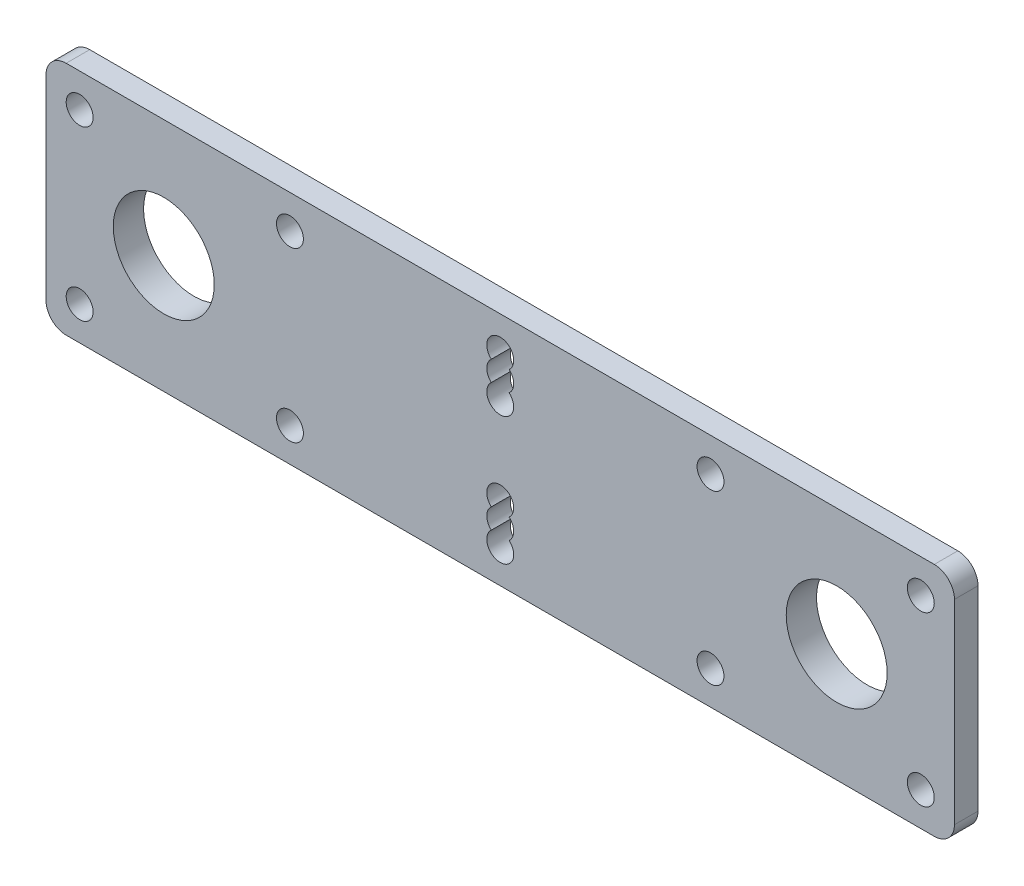
SolidWorks part; units mm, degrees
ref_plane "Ön Düzlem" through (0, 0, 0) normal (0, 0, 1) x (1, 0, 0)
ref_plane "Üst Düzlem" through (0, 0, 0) normal (0, 1, 0) x (1, 0, 0)
ref_plane "Sağ Düzlem" through (0, 0, 0) normal (1, 0, 0) x (0, 0, -1)
sketch "Sketch1" plane through (0, 0, 0) normal (0, 0, 1) x (1, 0, 0)
  line L1 (-135, 35) -> (135, 35)
  line L2 (-135, 35) -> (-135, -35)
  line L3 (-135, -35) -> (135, -35)
  line L4 (135, 35) -> (135, -35)
  line L5 (-135, 35) -> (135, -35) construction
  line L6 (-135, -35) -> (135, 35) construction
  point P0 (0, 0)
  dimension "D1" = 70
  dimension "D2" = 270
extrude "Boss-Extrude1" add sketch "Sketch1" along normal blind 7
fillet "Fillet1" radius 6 4 edges at (135, -35, 3.5) (135, 35, 3.5) (-135, -35, 3.5) (-135, 35, 3.5)
sketch "Sketch2" plane through (0, 0, 0) normal (0, 0, -1) x (-1, 0, 0)
  line L0 (-135, -29) -> (-135, 29) construction
  line L1 (135, 29) -> (135, -29) construction
  line L2 (-129, 35) -> (129, 35) construction
  line L4 (100, 0) -> (-100, 0) construction
  line L5 (125, 25) -> (-125, 25) construction
  line L6 (125, 25) -> (125, -25) construction
  line L7 (125, -25) -> (-125, -25) construction
  line L8 (-125, 25) -> (-125, -25) construction
  line L9 (125, 25) -> (-125, -25) construction
  line L10 (125, -25) -> (-125, 25) construction
  circle A0 centre (-100, 0) radius 15
  circle A1 centre (100, 0) radius 15
  circle A2 centre (125, 25) radius 4
  circle A3 centre (62.5, 25) radius 4
  arc A4 (2.6458, 22) -> (-2.6458, 22) centre (0, 25) ccw
  circle A5 centre (-62.5, 25) radius 4
  circle A6 centre (-125, 25) radius 4
  circle A7 centre (-125, -25) radius 4
  circle A8 centre (-62.5, -25) radius 4
  arc A9 (2.6458, -22) -> (-2.6458, -22) centre (0, -25) cw
  circle A10 centre (62.5, -25) radius 4
  circle A11 centre (125, -25) radius 4
  arc A13 (2.6458, 16) -> (2.6458, 22) centre (0, 19) ccw
  arc A14 (-2.6458, 16) -> (2.6458, 16) centre (0, 13) ccw
  arc A15 (-2.6458, -16) -> (2.6458, -16) centre (0, -13) cw
  arc A16 (2.6458, -16) -> (2.6458, -22) centre (0, -19) cw
  arc A17 (-2.6458, 22) -> (-2.6458, 16) centre (0, 19) ccw
  arc A18 (-2.6458, -22) -> (-2.6458, -16) centre (0, -19) cw
  point P9 (135, 0)
  point P10 (0, 0)
  dimension "D1" = 35
  dimension "D2" = 30
  dimension "D3" = 35
  dimension "D4" = 30
  dimension "D5" = 10
  dimension "D6" = 10
  dimension "D7" = 8
  dimension "D8" = 5
  dimension "D10" = 3
extrude "Cut-Extrude1" cut sketch "Sketch2" against normal blind 10
sketch "Sketch3" plane through (0, 0, 0) normal (0, 0, -1) x (-1, 0, 0)
  circle A0 centre (-100, 0) radius 15
  circle A1 centre (-100, 0) radius 20
  circle A2 centre (100, 0) radius 15
  circle A3 centre (100, 0) radius 20
  dimension "D1" = 40
  dimension "D2" = 40
extrude "Boss-Extrude2" add sketch "Sketch3" along normal blind 2
